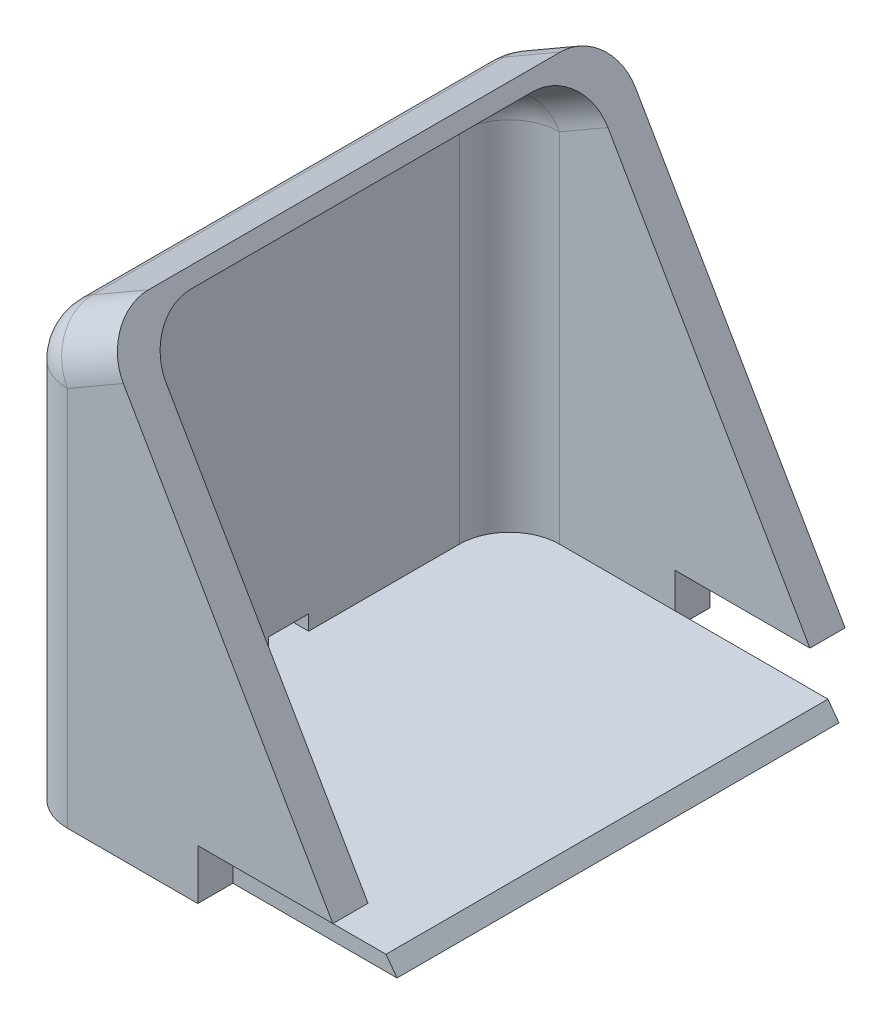
SolidWorks part; units mm, degrees
ref_plane "Ebene vorne" through (0, 0, 0) normal (0, 0, 1) x (1, 0, 0)
ref_plane "Ebene oben" through (0, 0, 0) normal (0, 1, 0) x (1, 0, 0)
ref_plane "Ebene rechts" through (0, 0, 0) normal (1, 0, 0) x (0, 0, -1)
sketch "Skizze1" plane through (0, 0, 0) normal (0, 0, 1) x (1, 0, 0)
  line L0 (0, 0) -> (50, 0)
  line L1 (50, 0) -> (-6.83, 98.4324)
  line L2 (-6.83, 98.4324) -> (-19.8204, 90.9324)
  line L3 (-19.8204, 90.9324) -> (26.906, 10)
  line L4 (26.906, 10) -> (0, 10)
  line L5 (0, 10) -> (0, 0)
  line L6 (0, 0) -> (-35.9254, 0)
  line L7 (-35.9254, 0) -> (-35.9254, 81.6342)
  line L8 (-35.9254, 81.6342) -> (-19.8204, 90.9324)
  line L9 (-35.9254, 0) -> (0, 0)
  dimension "D1" = 10
  dimension "D2" = 50
  dimension "D3" = 15
  dimension "D4" = 113.66
  dimension "D5" = 60
extrude "Aufsatz-Linear austragen1" add sketch "Skizze1" along normal blind 7 contours L8 L7 L6 L5 L4 L3
sketch "Skizze2" plane through (0, 0, 0) normal (0, 0, -1) x (-1, 0, 0)
  line L0 (35.9254, 0) -> (35.9254, 81.6342) construction
  line L1 (0, 0) -> (35.9254, 0)
  line L2 (0, 0) -> (0, 3)
  line L3 (0, 3) -> (35.9254, 3)
  line L4 (35.9254, 0) -> (35.9254, 3)
  dimension "D1" = 3
extrude "Aufsatz-Linear austragen2" add sketch "Skizze2" along normal blind 44
ref_plane "Ebene1" through (0, 0, -44) normal (0, 0, -1) x (-1, 0, 0)
mirror "Spiegeln3" about plane through (0, 0, -44) normal (0, 0, -1) of "Aufsatz-Linear austragen2"
sketch "Skizze4" plane through (0, 0, -88) normal (0, 0, -1) x (-1, 0, 0)
  line L0 (0, 3) -> (0, 0) construction
  line L1 (0, 0) -> (35.9254, 0) construction
  line L2 (35.9254, 0) -> (35.9254, 3) construction
  line L3 (35.9254, 3) -> (0, 3) construction
  line L4 (0, 3) -> (35.9254, 3) construction
  line L5 (35.9254, 3) -> (35.9254, 81.6342) construction
  line L6 (35.9254, 81.6342) -> (19.8204, 90.9324) construction
  line L7 (19.8204, 90.9324) -> (-26.906, 10) construction
  line L8 (-26.906, 10) -> (0, 10) construction
  line L9 (0, 10) -> (0, 3) construction
  line L10 (0, 3) -> (0, 0)
  line L11 (0, 0) -> (35.9254, 0)
  line L12 (35.9254, 0) -> (35.9254, 3)
  line L13 (35.9254, 3) -> (0, 3)
  line L14 (0, 3) -> (35.9254, 3)
  line L15 (35.9254, 3) -> (35.9254, 81.6342)
  line L16 (35.9254, 81.6342) -> (19.8204, 90.9324)
  line L17 (19.8204, 90.9324) -> (-26.906, 10)
  line L18 (-26.906, 10) -> (0, 10)
  line L19 (0, 10) -> (0, 3)
  line M1 (0, 3) -> (0, 0)
  line M2 (0, 0) -> (35.9254, 0)
  line M3 (35.9254, 0) -> (35.9254, 3)
  line M4 (35.9254, 3) -> (0, 3)
extrude "Aufsatz-Linear austragen3" add sketch "Skizze4" along normal blind 7 contours L18 L19 L15 L16 L17 M4 | M4 M1 M2 M3
ref_plane "Ebene2" through (0, 3, 0) normal (0, 0, 1) x (1, 0, 0)
sketch "Skizze6" plane through (0, 0, 0) normal (1, 0, 0) x (0, 0, -1)
  line L1 (0, 0) -> (88, 0)
  line L2 (0, 0) -> (0, 3)
  line L3 (0, 3) -> (88, 3)
  line L4 (88, 0) -> (88, 3)
extrude "Aufsatz-Linear austragen4" add sketch "Skizze6" along normal blind 32.68
sketch "Skizze7" plane through (0, 0, -88) normal (0, 0, 1) x (1, 0, 0)
  line L0 (-32.9254, 0) -> (-32.9254, 83.3662)
  line L1 (-35.9254, 81.6342) -> (-19.8204, 90.9324) construction
  line L2 (-35.9254, 78.1701) -> (-18.3204, 88.3344)
  line L6 (-19.8204, 90.9324) -> (-35.9254, 81.6342)
  line L7 (-35.9254, 81.6342) -> (-35.9254, 0)
  line L8 (-35.9254, 0) -> (0, 0)
  line L9 (0, 0) -> (0, 10)
  line L10 (0, 10) -> (26.906, 10)
  line L11 (26.906, 10) -> (-19.8204, 90.9324)
  line L12 (-19.8204, 90.9324) -> (-35.9254, 81.6342)
  line L13 (-35.9254, 81.6342) -> (-35.9254, 0)
  line L14 (-35.9254, 0) -> (0, 0)
  line L15 (0, 0) -> (0, 10)
  line L16 (0, 10) -> (26.906, 10)
  line L17 (26.906, 10) -> (-19.8204, 90.9324)
  line M9 (-35.9254, 81.6342) -> (-35.9254, 3)
  line M10 (-35.9254, 3) -> (0, 3)
  line M13 (26.906, 10) -> (-19.8204, 90.9324)
  line M14 (-19.8204, 90.9324) -> (-35.9254, 81.6342)
  dimension "D2" = 3
  dimension "D3" = 3
  dimension "D1" = 0
extrude "Aufsatz-Linear austragen5" add sketch "Skizze7" along normal up to surface (88 mm away) contours L2 L0 M9 M10 | L2 L0 M9 M14 | L0 L2 M13 M14 up to face at (-10.7942, 33.0944, 0)
sketch "Skizze8" plane through (-35.9254, 0, 0) normal (-1, 0, 0) x (0, 0, 1)
  line L0 (-44, 55) -> (-44, -55) construction
  line L1 (-48, 3) -> (-40, 3)
  line L2 (-48, 3) -> (-48, 6)
  line L3 (-48, 6) -> (-40, 6)
  line L4 (-40, 3) -> (-40, 6)
  line L5 (-48, 3) -> (-40, 6) construction
  line L6 (-48, 6) -> (-40, 3) construction
  line L7 (7, 0) -> (-95, 0) construction
  point P0 (-44, 4.5)
  dimension "D1" = 8
  dimension "D2" = 3
  dimension "D3" = 3
extrude "Schnitt-Linear austragen1" cut sketch "Skizze8" against normal up to surface (3 mm away) up to face at (-32.9254, 41.4511, -44)
fillet "Verrundung1" radius 10 5 edges at (-27.8729, 86.2833, 7) (-35.9254, 40.8171, 7) (-35.9254, 40.8171, -95) (-27.8729, 86.2833, -95) (-35.9254, 81.6342, -44)
fillet "Verrundung2" radius 10 5 edges at (-32.9254, 79.9021, -44) (-32.9254, 41.4511, 0) (-32.9254, 41.4511, -88) (-25.6229, 84.1183, -88) (-25.6229, 84.1183, 0)
sketch "Skizze9" plane through (0, 0, 0) normal (0, 0, 1) x (1, 0, 0)
  line L0 (32.68, 0) -> (30.4885, 3)
  line L1 (32.68, 3) -> (0, 3) construction
  line L2 (30.4885, 3) -> (32.68, 3)
  line L3 (32.68, 3) -> (32.68, 0)
extrude "Schnitt-Linear austragen2" cut sketch "Skizze9" against normal through all
